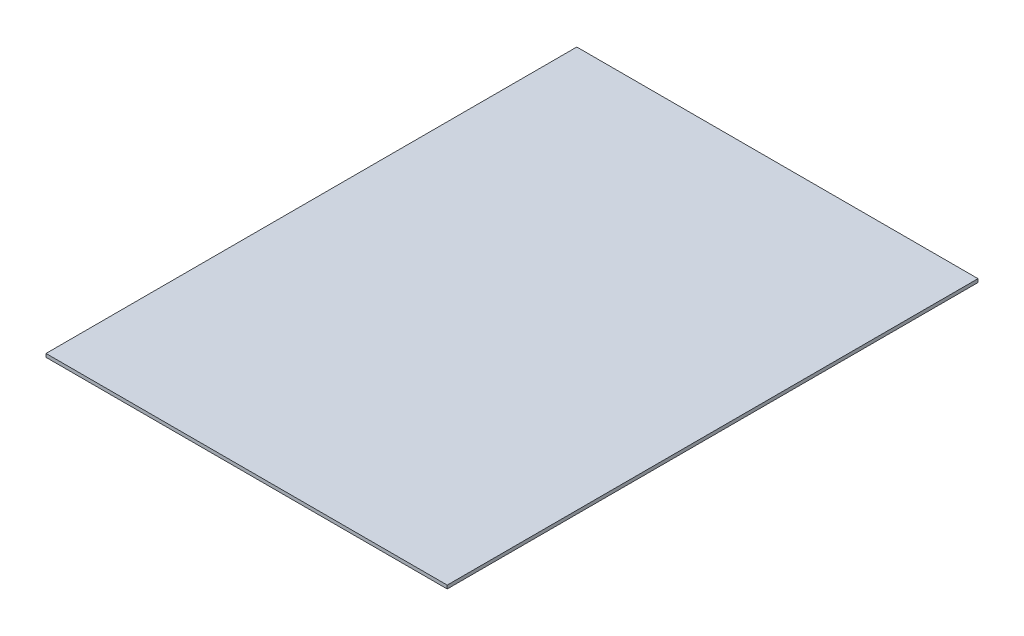
SolidWorks part; units mm, degrees
material "Acrylic (Medium-high impact)"
ref_plane "Front Plane" through (0, 0, 0) normal (0, 0, 1) x (1, 0, 0)
ref_plane "Top Plane" through (0, 0, 0) normal (0, 1, 0) x (1, 0, 0)
ref_plane "Right Plane" through (0, 0, 0) normal (1, 0, 0) x (0, 0, -1)
sketch "Sketch1" plane through (0, 0, 0) normal (0, 1, 0) x (1, 0, 0)
  line L1 (-187.198, -247.65) -> (187.198, -247.65)
  line L2 (-187.198, -247.65) -> (-187.198, 247.65)
  line L3 (-187.198, 247.65) -> (187.198, 247.65)
  line L4 (187.198, -247.65) -> (187.198, 247.65)
  line L5 (-187.198, -247.65) -> (187.198, 247.65) construction
  line L6 (-187.198, 247.65) -> (187.198, -247.65) construction
  point P0 (0, 0)
  dimension "D1" = 374.396
  dimension "D2" = 495.3
extrude "Boss-Extrude1" add sketch "Sketch1" along normal mid plane 3.175
